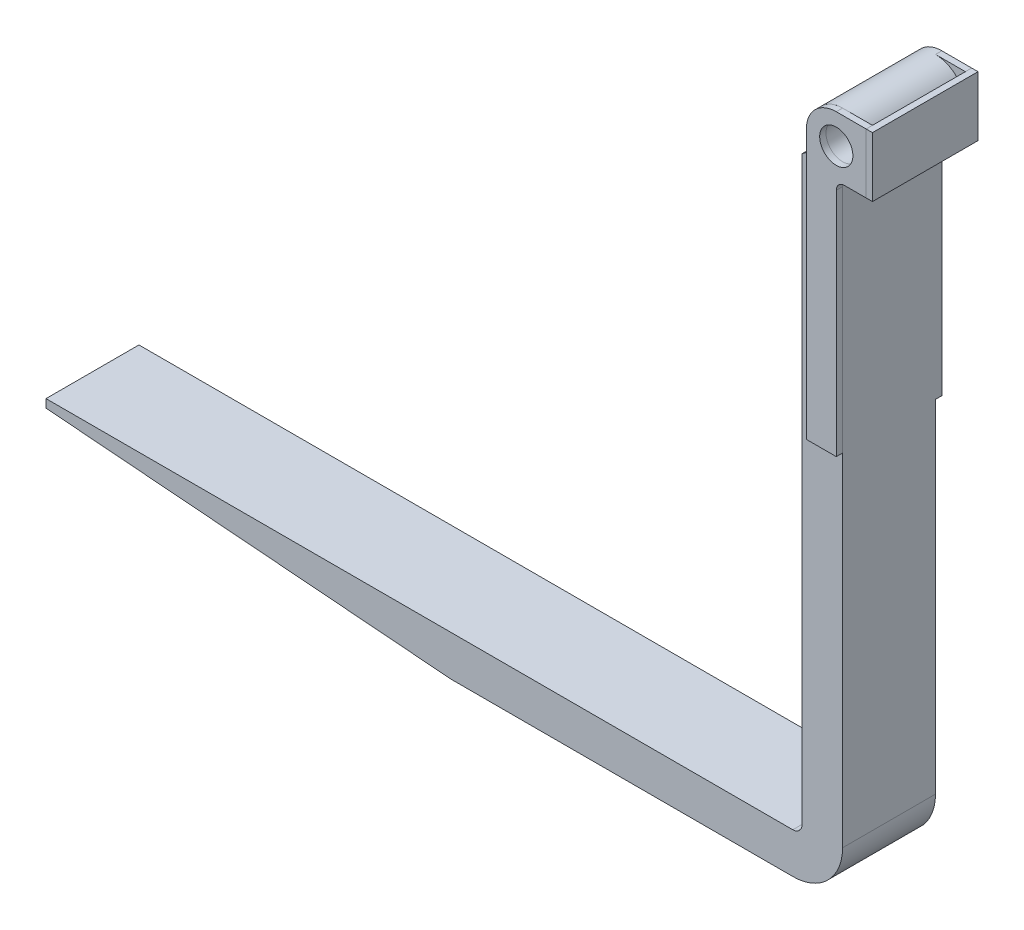
SolidWorks part; units mm, degrees
ref_plane "Front Plane" through (0, 0, 0) normal (0, 0, 1) x (1, 0, 0)
ref_plane "Top Plane" through (0, 0, 0) normal (0, 1, 0) x (1, 0, 0)
ref_plane "Right Plane" through (0, 0, 0) normal (1, 0, 0) x (0, 0, -1)
sketch "Sketch1" plane through (0, 0, 0) normal (0, 0, 1) x (1, 0, 0)
  line L0 (0, 950) -> (0, 75)
  line L1 (-75, 0) -> (-1200, 0)
  arc A0 (0, 75) -> (-75, 0) centre (-75, 75) cw
  point P6 (0, 0)
  dimension "D3" = 75
  dimension "D1" = 950
  dimension "D2" = 1200
extrude "Extrude-Thin1" add sketch "Sketch1" along normal mid plane 140 thin
sketch "Sketch2" plane through (0, 0, 70) normal (0, 0, 1) x (1, 0, 0)
  line L0 (-1200, 48.5) -> (-590, 0)
  line L2 (-1200, 0) -> (-1200, 61) construction
  line L3 (-75, 0) -> (-1200, 0) construction
  dimension "D1" = 12.5
  dimension "D2" = 610
extrude "Cut-Extrude1" cut sketch "Sketch2" against normal through all and the other way through all flip side to cut
sketch "Sketch3" plane through (0, 0, 0) normal (0, 0, 1) x (1, 0, 0)
  line L0 (0, 950) -> (0, 995) construction
  circle A0 centre (0, 995) radius 45
  circle A1 centre (0, 995) radius 25
  dimension "D1" = 50
  dimension "D2" = 90
extrude "Boss-Extrude1" add sketch "Sketch3" along normal mid plane 140 separate body
sketch "Sketch4" plane through (0, 0, 0) normal (0, 0, 1) x (1, 0, 0)
  line L0 (-61, 950) -> (0, 950) construction
  line L1 (-61, 950) -> (0, 950)
  line L2 (-61, 950) -> (-36.2126, 968.2858)
  circle A0 centre (0, 995) radius 45 construction
  circle A1 centre (0, 995) radius 45
extrude "Boss-Extrude2" add sketch "Sketch4" along normal mid plane 140 separate body contours A1 L2 L1
sketch "Sketch5" plane through (0, 0, 70) normal (0, 0, 1) x (1, 0, 0)
  line L0 (-45, 995) -> (-45, 590)
  line L1 (-45, 590) -> (0, 590)
  line L2 (0, 950) -> (0, 75) construction
  line L3 (0, 590) -> (0, 937.5)
  line L4 (12.5, 950) -> (45, 950)
  line L5 (45, 950) -> (45, 1040)
  line L6 (45, 1040) -> (0, 1040)
  circle A0 centre (0, 995) radius 45 construction
  arc A1 (-45, 995) -> (0, 1040) centre (0, 995) cw
  arc A2 (0, 937.5) -> (12.5, 950) centre (12.5, 937.5) cw
  point P16 (0, 950)
  circle M1 centre (0, 995) radius 45
  circle M2 centre (0, 995) radius 25
  dimension "D1" = 12.5
  dimension "D2" = 45
  dimension "D3" = 450
extrude "Boss-Extrude3" add sketch "Sketch5" along normal blind 9.5 separate body contours M1 M2 | L3 A2 L4 L5 L0 L1 M1 | L5 L6 M1
mirror "Mirror1" about plane through (0, 0, 0) normal (0, 0, 1) of "Boss-Extrude3"
sketch "Sketch6" plane through (45, 0, 0) normal (1, 0, 0) x (0, 0, -1)
  line L1 (-79.5, 1040) -> (79.5, 1040)
  line L2 (-79.5, 1040) -> (-79.5, 950)
  line L3 (-79.5, 950) -> (79.5, 950)
  line L4 (79.5, 1040) -> (79.5, 950)
extrude "Boss-Extrude4" add sketch "Sketch6" along normal blind 9.5 separate body
